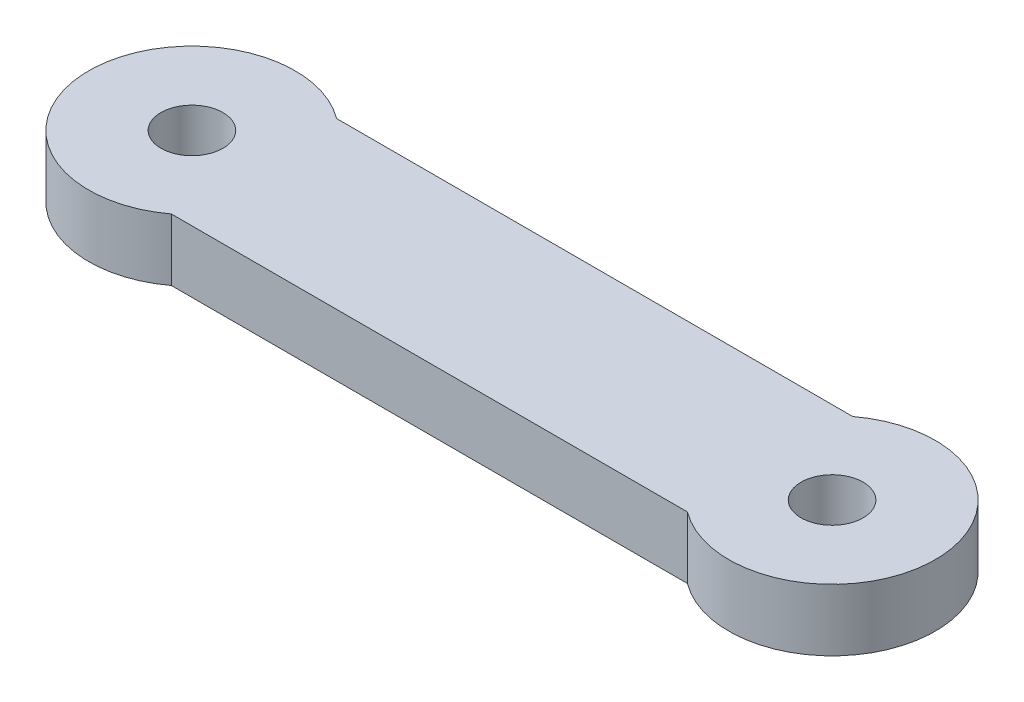
SolidWorks part; units mm, degrees
ref_plane "Alzado" through (0, 0, 0) normal (0, 0, 1) x (1, 0, 0)
ref_plane "Planta" through (0, 0, 0) normal (0, 1, 0) x (1, 0, 0)
ref_plane "Vista lateral" through (0, 0, 0) normal (1, 0, 0) x (0, 0, -1)
sketch "Croquis1" plane through (0, 0, 0) normal (0, 1, 0) x (1, 0, 0)
  line L0 (-12.4902, 4) -> (12.4902, 4)
  line L2 (12.4902, -4) -> (-12.4902, -4)
  circle A0 centre (-15.4902, 0) radius 1.5
  arc A1 (-12.4902, 4) -> (-12.4902, -4) centre (-15.4902, 0) ccw
  circle A2 centre (15.4902, 0) radius 1.5
  arc A3 (12.4902, 4) -> (12.4902, -4) centre (15.4902, 0) cw
  dimension "D1" = 3
  dimension "D2" = 10
  dimension "D6" = 5
  dimension "D9" = 3
  dimension "D3" = 4
  dimension "D4" = 4
  dimension "D5" = 30.9804
  dimension "D7" = 15.4902
extrude "Saliente-Extruir1" add sketch "Croquis1" along normal blind 3
